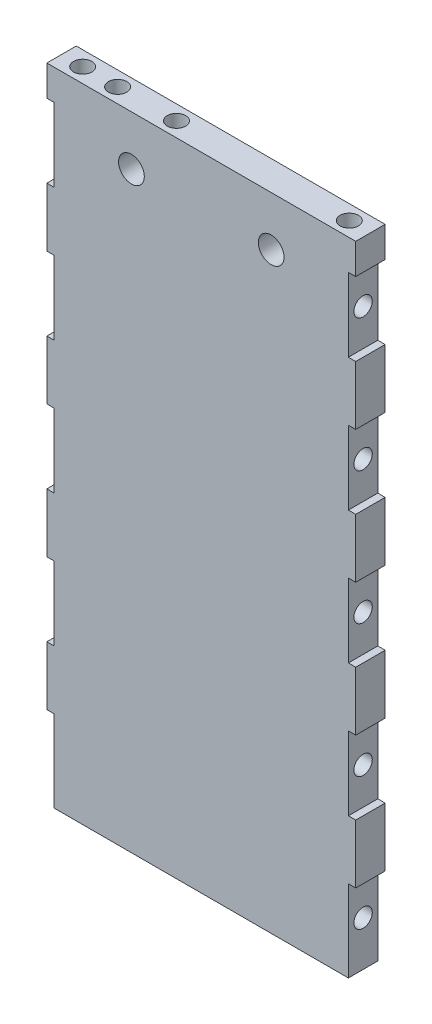
SolidWorks part; units mm, degrees
ref_plane "Front Plane" through (0, 0, 0) normal (0, 0, 1) x (1, 0, 0)
ref_plane "Top Plane" through (0, 0, 0) normal (0, 1, 0) x (1, 0, 0)
ref_plane "Right Plane" through (0, 0, 0) normal (1, 0, 0) x (0, 0, -1)
sketch "Sketch1" plane through (0, 0, 0) normal (0, 0, 1) x (1, 0, 0)
  line L0 (0, 22.2) -> (2, 22.2)
  line L1 (2, 0) -> (82, 0)
  line L2 (0, 22.2) -> (0, 38.2)
  line L3 (0, 174.5) -> (84, 174.5)
  line L4 (84, 22.2) -> (84, 38.2)
  line L5 (2, 22.2) -> (2, 0)
  line L6 (0, 38.2) -> (2, 38.2)
  line L7 (2, 58.2) -> (2, 38.2)
  line L8 (2, 58.2) -> (0, 58.2)
  line L9 (0, 74.2) -> (2, 74.2)
  line L10 (2, 94.2) -> (2, 74.2)
  line L11 (2, 94.2) -> (0, 94.2)
  line L12 (0, 110.2) -> (2, 110.2)
  line L13 (2, 130.2) -> (2, 110.2)
  line L14 (2, 130.2) -> (0, 130.2)
  line L15 (0, 146.2) -> (2, 146.2)
  line L16 (2, 166.2) -> (2, 146.2)
  line L17 (2, 166.2) -> (0, 166.2)
  line L18 (42, 0) -> (42, 174.5) construction
  line L19 (84, 58.2) -> (84, 74.2)
  line L20 (84, 94.2) -> (84, 110.2)
  line L21 (84, 130.2) -> (84, 146.2)
  line L22 (82, 166.2) -> (84, 166.2)
  line L23 (82, 166.2) -> (82, 146.2)
  line L24 (84, 146.2) -> (82, 146.2)
  line L25 (82, 130.2) -> (84, 130.2)
  line L26 (82, 130.2) -> (82, 110.2)
  line L27 (84, 110.2) -> (82, 110.2)
  line L28 (82, 94.2) -> (84, 94.2)
  line L29 (82, 94.2) -> (82, 74.2)
  line L30 (84, 74.2) -> (82, 74.2)
  line L31 (82, 58.2) -> (84, 58.2)
  line L32 (82, 58.2) -> (82, 38.2)
  line L33 (0, 166.2) -> (0, 174.5)
  line L34 (0, 130.2) -> (0, 146.2)
  line L35 (0, 94.2) -> (0, 110.2)
  line L36 (0, 58.2) -> (0, 74.2)
  line L37 (84, 38.2) -> (82, 38.2)
  line L38 (82, 22.2) -> (82, 0)
  line L39 (84, 22.2) -> (84, 38.2)
  line L40 (84, 22.2) -> (82, 22.2)
  line L41 (84, 166.2) -> (84, 174.5)
  line L42 (84, 130.2) -> (84, 146.2)
  line L43 (84, 94.2) -> (84, 110.2)
  line L44 (84, 58.2) -> (84, 74.2)
  point P6 (42, 174.5)
  dimension "D1" = 84
  dimension "D2" = 174.5
  dimension "D3" = 2
  dimension "D4" = 2
  dimension "D5" = 22.2
  dimension "D6" = 16
  dimension "D7" = 20
extrude "Boss-Extrude1" add sketch "Sketch1" along normal blind 8 contours L1 L18 L3 L33 L17 L16 L15 L34 L14 L13 L12 L35 L11 L10 L9 L36 L8 L7 L6 L2 L0 L5 | L18 L1 L38 L40 L4 L37 L32 L31 L19 L30 L29 L28 L20 L27 L26 L25 L21 L24 L23 L22 L41 L3
sketch "Sketch2" plane through (2, 0, 0) normal (-1, 0, 0) x (0, 0, 1)
  line L0 (0, 166.2) -> (0, 146.2) construction
  line L3 (8, 166.2) -> (0, 166.2) construction
  circle A0 centre (4, 156.2) radius 2.5
  circle A1 centre (4, 120.2) radius 2.5
  circle A2 centre (4, 84.2) radius 2.5
  circle A3 centre (4, 48.2) radius 2.5
  circle A4 centre (4, 12.2) radius 2.5
  point P6 (0, 156.2)
  point P9 (4, 166.2)
  dimension "D1" = 5
  dimension "D2" = 5
extrude "Cut-Extrude1" cut sketch "Sketch2" against normal blind 10
ref_plane "Plane1" through (42, 0, 0) normal (1, 0, 0) x (0, 0, -1)
mirror "Mirror1" about plane through (42, 0, 0) normal (1, 0, 0) of "Cut-Extrude1"
sketch "Sketch3" plane through (0, 0, 0) normal (0, -1, 0) x (1, 0, 0)
  line L0 (42, -95.975) -> (42, 95.975) construction
  line L1 (2, 8) -> (82, 8) construction
  circle A0 centre (42, 4) radius 2
  circle A1 centre (76, 4) radius 2
  circle A2 centre (8, 4) radius 2
  dimension "D1" = 4
  dimension "D2" = 4
  dimension "D3" = 2
extrude "Cut-Extrude2" cut sketch "Sketch3" against normal blind 8
sketch "Sketch4" plane through (0, 174.5, 0) normal (0, 1, 0) x (1, 0, 0)
  line L0 (0, -8) -> (0, 0) construction
  line L1 (0, 0) -> (84, 0) construction
  line L2 (42, -95.975) -> (42, 95.975) construction
  circle A0 centre (5.75, -4) radius 2.5
  circle A1 centre (78.25, -4) radius 2.5
  dimension "D1" = 5.75
  dimension "D3" = 5
  dimension "D2" = 4
extrude "Cut-Extrude3" cut sketch "Sketch4" against normal blind 10
sketch "Sketch5" plane through (0, 174.5, 0) normal (0, 1, 0) x (1, 0, 0)
  line L0 (5.75, -4) -> (31.25, -4) construction
  circle A0 centre (15.25, -4) radius 2.5
  circle A1 centre (31.25, -4) radius 2.5
  circle A2 centre (5.75, -4) radius 2.5 construction
  dimension "D1" = 16
  dimension "D3" = 5
  dimension "D4" = 5
  dimension "D2" = 9.5
extrude "Cut-Extrude4" cut sketch "Sketch5" against normal blind 10
sketch "Sketch6" plane through (0, 0, 8) normal (0, 0, 1) x (1, 0, 0)
  line L0 (0, 174.5) -> (84, 174.5) construction
  line L1 (42, -95.975) -> (42, 95.975) construction
  circle A0 centre (23, 161) radius 3.5
  circle A1 centre (61, 161) radius 3.5
  dimension "D1" = 13.5
  dimension "D2" = 7
  dimension "D3" = 19
extrude "Cut-Extrude5" cut sketch "Sketch6" against normal blind 8
